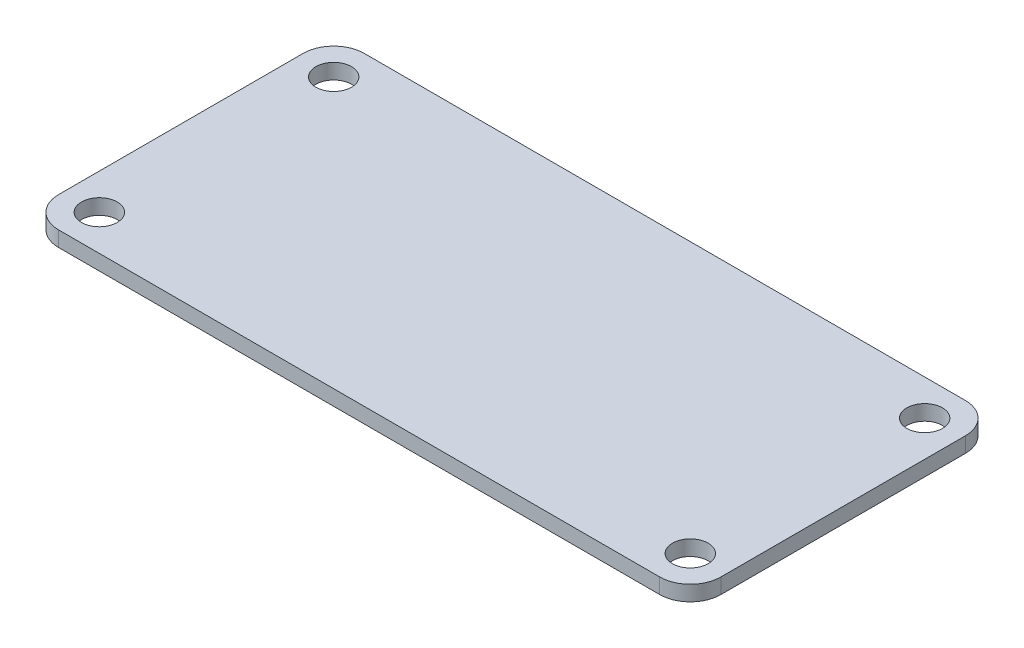
SolidWorks part; units mm, degrees
ref_plane "前视基准面" through (0, 0, 0) normal (0, 0, 1) x (1, 0, 0)
ref_plane "上视基准面" through (0, 0, 0) normal (0, 1, 0) x (1, 0, 0)
ref_plane "右视基准面" through (0, 0, 0) normal (1, 0, 0) x (0, 0, -1)
sketch "草图1" plane through (0, 0, 0) normal (0, 1, 0) x (1, 0, 0)
  line L1 (-32.5, 15) -> (32.5, 15)
  line L2 (-32.5, 15) -> (-32.5, -15)
  line L3 (-32.5, -15) -> (32.5, -15)
  line L4 (32.5, 15) -> (32.5, -15)
  line L5 (0, -15) -> (0, 15) construction
  line L6 (-32.5, 0) -> (32.5, 0) construction
  circle A0 centre (-29, 11.5) radius 1.75
  circle A1 centre (29, 11.5) radius 1.75
  circle A2 centre (29, -11.5) radius 1.75
  circle A3 centre (-29, -11.5) radius 1.75
  point P0 (0, 0)
  dimension "D3" = 58
  dimension "D4" = 23
  dimension "D5" = 3.5
  dimension "D1" = 65
  dimension "D2" = 30
extrude "凸台-拉伸1" add sketch "草图1" along normal blind 1.5
fillet "圆角1" radius 3 4 edges at (-32.5, 0.75, -15) (32.5, 0.75, -15) (32.5, 0.75, 15) (-32.5, 0.75, 15)
equation "\"m\"= 2"
